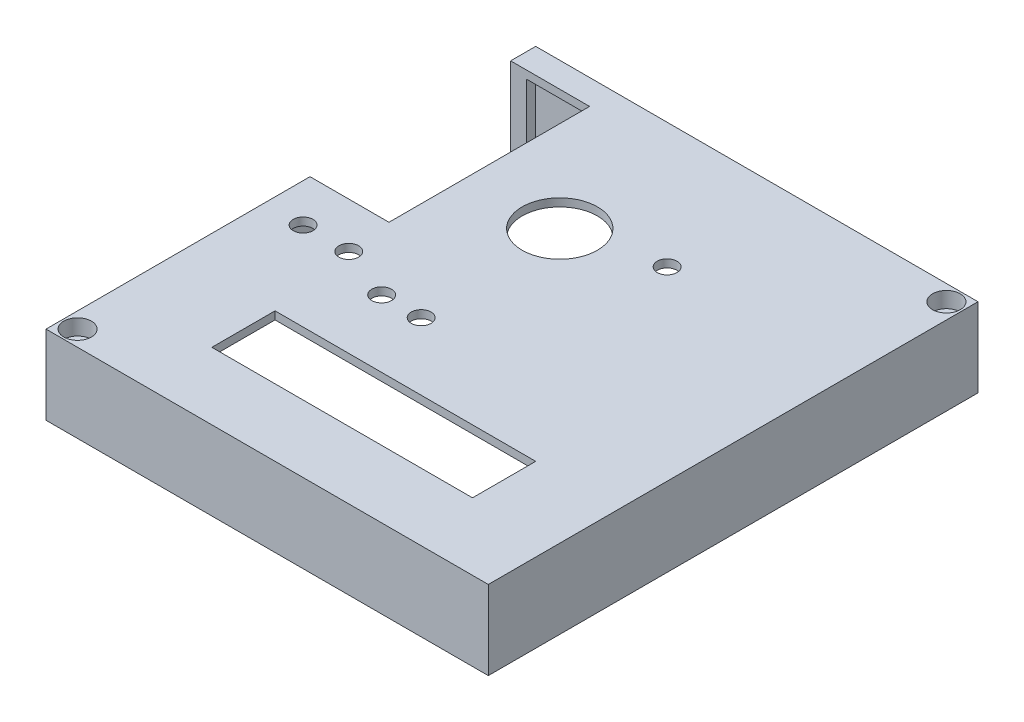
SolidWorks part; units mm, degrees
ref_plane "Front Plane" through (0, 0, 0) normal (0, 0, 1) x (1, 0, 0)
ref_plane "Top Plane" through (0, 0, 0) normal (0, 1, 0) x (1, 0, 0)
ref_plane "Right Plane" through (0, 0, 0) normal (1, 0, 0) x (0, 0, -1)
sketch "Sketch1" plane through (0, 0, 0) normal (0, 1, 0) x (1, 0, 0)
  line L1 (-56, -62) -> (56, -62)
  line L2 (-56, -62) -> (-56, 62)
  line L3 (-56, 62) -> (56, 62)
  line L4 (56, -62) -> (56, 62)
  line L5 (-56, -62) -> (56, 62) construction
  line L6 (-56, 62) -> (56, -62) construction
  point P0 (0, 0)
  dimension "D1" = 112
  dimension "D2" = 124
extrude "Boss-Extrude1" add sketch "Sketch1" along normal blind 2
sketch "Sketch4" plane through (0, 0, 0) normal (0, -1, 0) x (1, 0, 0)
  line L0 (-48, 58) -> (-48, 54)
  line L1 (-48, 54) -> (-52, 54)
  line L2 (48, -58) -> (48, -54)
  line L3 (48, -54) -> (52, -54)
  line L4 (56, -62) -> (56, 62)
  line L5 (56, 62) -> (-56, 62)
  line L6 (-56, 62) -> (-56, -62)
  line L7 (-56, -62) -> (56, -62)
  line L8 (56, -62) -> (56, 62)
  line L9 (56, 62) -> (-56, 62)
  line L10 (-56, 62) -> (-56, -62)
  line L11 (-56, -62) -> (56, -62)
  line L24 (52, -58) -> (52, 58)
  line L25 (52, 58) -> (-52, 58)
  line L26 (-52, 58) -> (-52, -58)
  line L27 (-52, -58) -> (52, -58)
  line L28 (52, -54) -> (52, 58)
  line L29 (52, 58) -> (-48, 58)
  line L30 (-52, 54) -> (-52, -58)
  line L31 (-52, -58) -> (48, -58)
  dimension "D4" = 4
  dimension "D6" = 4
  dimension "D1" = 0
  dimension "D2" = 4
extrude "Boss-Extrude2" add sketch "Sketch4" along normal blind 18
sketch "Sketch5" plane through (0, 2, 0) normal (0, 1, 0) x (1, 0, 0)
  line L0 (-56, -62) -> (56, -62) construction
  line L1 (-31, -45) -> (35, -45)
  line L2 (-31, -45) -> (-31, -29)
  line L3 (-31, -29) -> (35, -29)
  line L4 (35, -45) -> (35, -29)
  line L5 (-31, -45) -> (35, -29) construction
  line L6 (-31, -29) -> (35, -45) construction
  line L7 (56, 62) -> (-56, 62) construction
  line L8 (56, -62) -> (56, 62) construction
  line L10 (-56, 62) -> (-56, -62) construction
  circle A0 centre (-13, 25.1) radius 9.525
  circle A1 centre (-46.27, -6.63) radius 2.5
  circle A2 centre (-34.7, -6.63) radius 2.5
  circle A3 centre (-21, -12) radius 2.5
  circle A4 centre (-11, -12) radius 2.5
  circle A5 centre (9, 30.28) radius 2.5
  point P0 (2, -37)
  dimension "D4" = 19.05
  dimension "D8" = 5
  dimension "D9" = 5
  dimension "D1" = 66
  dimension "D2" = 16
  dimension "D3" = 17
  dimension "D5" = 36.9
  dimension "D6" = 43
  dimension "D7" = 25
  dimension "D10" = 9.73
  dimension "D11" = 21.3
  dimension "D12" = 47
  dimension "D13" = 31.72
  dimension "D14" = 35
  dimension "D15" = 45
  dimension "D16" = 55.37
  dimension "D17" = 50
extrude "Cut-Extrude1" cut sketch "Sketch5" against normal up to next
sketch "Sketch6" plane through (0, 2, 0) normal (0, 1, 0) x (1, 0, 0)
  line L0 (56, 62) -> (-56, 62) construction
  line L1 (56, -62) -> (56, 62) construction
  line L2 (-56, -62) -> (56, -62) construction
  line L3 (-56, 62) -> (-56, -62) construction
  circle A0 centre (52, 58) radius 2
  circle A1 centre (-52, -58) radius 2
  dimension "D1" = 4
  dimension "D4" = 4
  dimension "D2" = 4
  dimension "D3" = 4
  dimension "D5" = 4
  dimension "D6" = 4
extrude "Cut-Extrude2" cut sketch "Sketch6" against normal through all
sketch "Sketch7" plane through (0, 2, 0) normal (0, 1, 0) x (1, 0, 0)
  circle A0 centre (-52, -58) radius 3.5
  circle A1 centre (52, 58) radius 3.5
  dimension "D1" = 7
  dimension "D2" = 7
extrude "Cut-Extrude3" cut sketch "Sketch7" against normal blind 4
sketch "Sketch8" plane through (-56, 0, 0) normal (-1, 0, 0) x (0, 0, 1)
  line L0 (-62, 2) -> (62, 2) construction
  line L1 (-55.65, 2) -> (-4.85, 2)
  line L2 (-55.65, 2) -> (-55.65, -18)
  line L3 (-55.65, -18) -> (-4.85, -18)
  line L4 (-4.85, 2) -> (-4.85, -18)
  line L5 (62, -18) -> (-62, -18) construction
  line L6 (-62, 2) -> (-62, -18) construction
  dimension "D1" = 6.35
  dimension "D2" = 50.8
extrude "Cut-Extrude4" cut sketch "Sketch8" against normal blind 20
